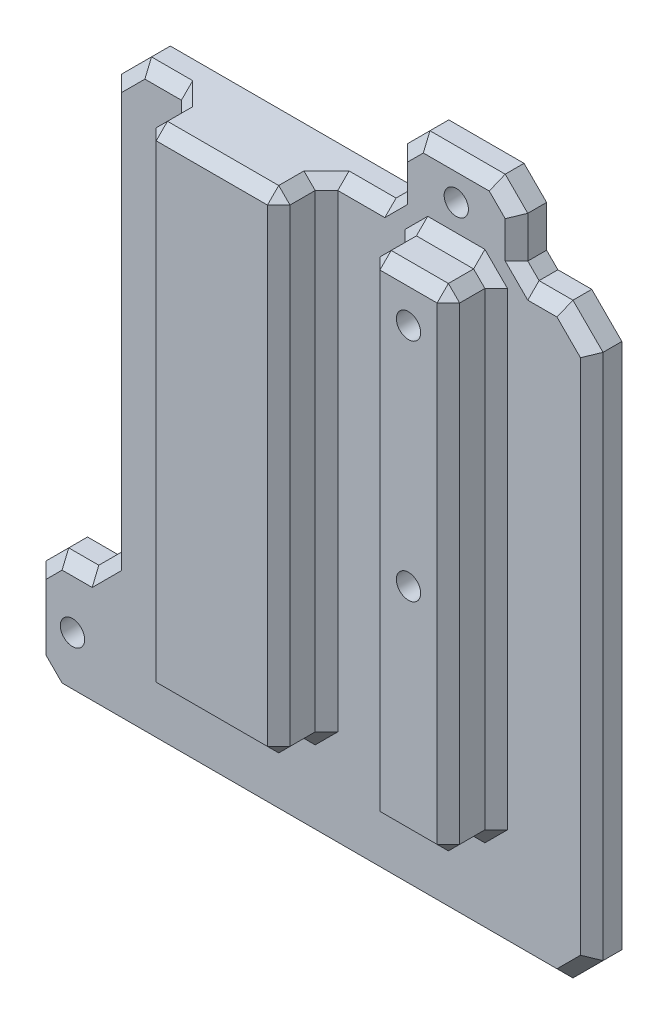
SolidWorks part; units mm, degrees
material "PET"
ref_plane "Front Plane" through (0, 0, 0) normal (0, 0, 1) x (1, 0, 0)
ref_plane "Top Plane" through (0, 0, 0) normal (0, 1, 0) x (1, 0, 0)
ref_plane "Right Plane" through (0, 0, 0) normal (1, 0, 0) x (0, 0, -1)
sketch "Sketch1" plane through (0, 0, 0) normal (0, 0, 1) x (1, 0, 0)
  line L0 (-16, 177.3) -> (16, 177.3) construction
  line L1 (16, 177.3) -> (16, 138.3) construction
  line L2 (16, 138.3) -> (-16, 138.3) construction
  line L3 (-16, 138.3) -> (-16, 177.3) construction
  line L4 (16, 177.3) -> (16, 138.3)
  line L5 (16, 138.3) -> (-16, 138.3)
  line L6 (-16, 138.3) -> (-16, 177.3)
  line L7 (-16, 177.3) -> (16, 177.3)
extrude "Boss-Extrude1" add sketch "Sketch1" along normal blind 2
sketch "Sketch2" plane through (0, 0, 2) normal (0, 0, 1) x (1, 0, 0)
  line L0 (7, 174.3) -> (7, 159.3) construction
  line L1 (-16, 177.3) -> (16, 177.3) construction
  line L2 (4.35, 144.65) -> (9.65, 144.65)
  line L3 (4.35, 144.65) -> (4.35, 177.3)
  line L4 (4.35, 177.3) -> (9.65, 177.3)
  line L5 (9.65, 144.65) -> (9.65, 177.3)
  line L6 (4.35, 144.65) -> (9.65, 177.3) construction
  line L7 (4.35, 177.3) -> (9.65, 144.65) construction
  line L8 (16, 138.3) -> (-16, 138.3) construction
  line L9 (16, 177.3) -> (16, 138.3) construction
  line L10 (-6.068, 161.726) -> (-6.068, 177.3) construction
  line L11 (-0.678, 161.726) -> (-11.458, 161.726) construction
  line L13 (-10.513, 144.65) -> (-1.623, 144.65)
  line L14 (-10.513, 144.65) -> (-10.513, 177.3)
  line L15 (-10.513, 177.3) -> (-1.623, 177.3)
  line L16 (-1.623, 144.65) -> (-1.623, 177.3)
  line L17 (-10.513, 144.65) -> (-1.623, 177.3) construction
  line L18 (-10.513, 177.3) -> (-1.623, 144.65) construction
  circle A0 centre (-13.688, 175.296) radius 0.254 construction
  point P4 (7, 160.975)
  point P19 (-6.068, 160.975)
  dimension "D1" = 6.35
  dimension "D2" = 6.35
  dimension "D3" = 3.175
extrude "Boss-Extrude2" add sketch "Sketch2" along normal blind 3.175
sketch "Sketch10" plane through (0, 0, 2) normal (0, 0, 1) x (1, 0, 0)
  line L0 (7, 177.3) -> (7, 182.3) construction
  line L1 (9.65, 177.3) -> (4.35, 177.3) construction
  line L3 (11, 177.3) -> (3, 177.3)
  line L4 (11, 177.3) -> (11, 182.3)
  line L5 (11, 182.3) -> (3, 182.3)
  line L6 (3, 177.3) -> (3, 182.3)
  line L7 (11, 177.3) -> (3, 182.3) construction
  line L8 (11, 182.3) -> (3, 177.3) construction
  line L9 (-16, 138.3) -> (-21, 138.3)
  line L10 (-16, 138.3) -> (-16, 146.3)
  line L11 (-16, 146.3) -> (-21, 146.3)
  line L12 (-21, 138.3) -> (-21, 146.3)
  point P4 (7, 179.8)
  dimension "D1" = 8
  dimension "D2" = 5
extrude "Boss-Extrude3" add sketch "Sketch10" against normal up to surface (2 mm away) up to face at (0, 157.8, 0)
hole_wizard "#52 (0.0635) Diameter Hole1" positions "Sketch3" profile "Sketch4" hole size "#52" standard "ANSI Inch" end condition through all
sketch "Sketch3" plane through (0, 0, 5.175) normal (0, 0, 1) x (1, 0, 0)
  line L0 (-16, 146.3) -> (-21, 138.3) construction
  line L2 (11, 177.3) -> (11, 182.3) construction
  point P0 (7, 174.3)
  point P3 (7, 159.3)
  point P13 (-18.5, 142.3)
  point P22 (7, 179.8)
  point P26 (0, 0)
  point P27 (7, 179.4205)
  point P30 (11, 179.8)
  point P31 (0, 0)
sketch "Sketch4" plane through (7, 174.3, 5.175) normal (1, 0, 0) x (0, -1, 0)
  line L0 (0, 0) -> (0, 5.175)
  line L1 (0, 5.175) -> (0.8064, 5.175)
  line L2 (0.8064, 5.175) -> (0.8064, 0)
  line L5 (0.8064, 0) -> (0, 0)
  line L11 (0, -6.35) -> (0, 107.95) construction
  dimension "Thru Hole Dia." = 1.6129
  dimension "Thru Hole Depth" = 5.175
chamfer "Chamfer1" distance 2 angle 45 3 edges at (16, 177.3, 1) (16, 138.3, 1) (-16, 177.3, 1)
chamfer "Chamfer3" distance 1.5 angle 45 5 edges at (11, 182.3, 1) (3, 182.3, 1) (-21, 138.3, 1) (-21, 146.3, 1) (-16, 146.3, 1)
chamfer "Chamfer2" distance 0.75 angle 45 44 edges at (-21, 142.3, 2) (7, 182.3, 2) (3, 179.05, 2) (-18.5, 146.3, 2) (-2.75, 138.3, 2) (3.75, 181.55, 2) (10.25, 181.55, 2) (-20.25, 145.55, 2) (-20.25, 139.05, 2) (-16.75, 147.05, 2) (9.65, 160.975, 2) (9.65, 144.65, 3.5875) (9.65, 177.3, 3.5875) (4.35, 160.975, 2) (4.35, 177.3, 3.5875) (7, 144.65, 2) (4.35, 144.65, 3.5875) (9.65, 160.975, 5.175) (7, 177.3, 5.175) (4.35, 160.975, 5.175) (7, 144.65, 5.175) (-12.2565, 177.3, 2) (-1.623, 160.975, 2) (-1.623, 144.65, 3.5875) (-1.623, 177.3, 3.5875) (-10.513, 160.975, 2) (-10.513, 177.3, 3.5875) (-6.068, 144.65, 2) (-10.513, 144.65, 3.5875) (-1.623, 160.975, 5.175) (-6.068, 177.3, 5.175) (-10.513, 160.975, 5.175) (-6.068, 144.65, 5.175) (0.6885, 177.3, 2) (7, 177.3, 2) (11, 179.05, 2) (11, 177.3, 1) (3, 177.3, 1) (12.5, 177.3, 2) (16, 157.8, 2) (-16, 161.55, 2) (-15, 176.3, 2) (15, 139.3, 2) (15, 176.3, 2)
